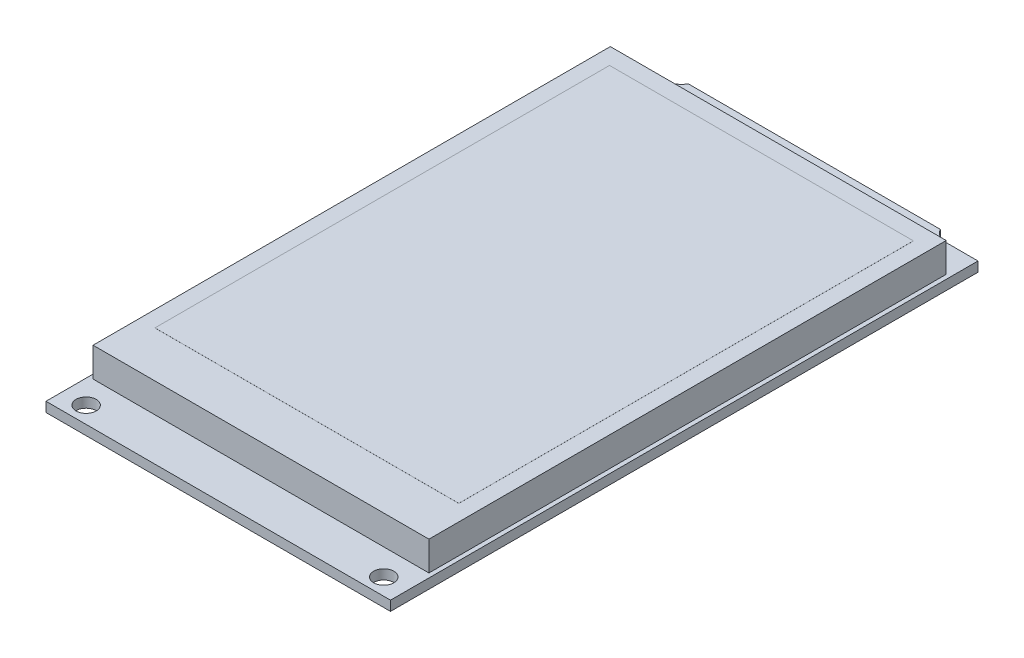
SolidWorks part; units mm, degrees
ref_plane "前视基准面" through (0, 0, 0) normal (0, 0, 1) x (1, 0, 0)
ref_plane "上视基准面" through (0, 0, 0) normal (0, 1, 0) x (1, 0, 0)
ref_plane "右视基准面" through (0, 0, 0) normal (1, 0, 0) x (0, 0, -1)
sketch "草图1" plane through (0, 0, 0) normal (0, 1, 0) x (1, 0, 0)
  line L0 (27.1813, 0) -> (83.5913, 0)
  line L1 (83.5913, 0) -> (83.5913, 96.2)
  line L2 (83.5913, 96.2) -> (78.2655, 96.2)
  line L3 (27.1813, 96.2) -> (27.1813, 0)
  line L5 (55.3863, 97.6) -> (34.7463, 97.6)
  line L6 (55.3863, 97.6) -> (76.0263, 97.6)
  line L7 (32.5072, 96.2) -> (27.1813, 96.2)
  arc A0 (76.0263, 97.6) -> (78.2655, 96.2) centre (78.353, 98.8306) ccw
  arc A1 (34.7463, 97.6) -> (32.5072, 96.2) centre (32.4197, 98.8306) cw
  circle A2 centre (31.0213, 2.73) radius 1.65
  circle A3 centre (79.7513, 2.73) radius 1.65
extrude "凸台-拉伸1" add sketch "草图1" along normal blind 1.6
sketch "草图3" plane through (0, 1.6, 0) normal (0, 1, 0) x (1, 0, 0)
  line L2 (55.3863, 7) -> (27.8863, 7)
  line L3 (55.3863, 7) -> (82.8863, 7)
  line L4 (82.8863, 7) -> (82.8863, 91.7)
  line L5 (27.8863, 7) -> (27.8863, 91.7)
  line L6 (27.8863, 91.7) -> (82.8863, 91.7)
extrude "凸台-拉伸2" add sketch "草图3" along normal blind 4.8
sketch "草图4" plane through (0, 6.4, 0) normal (0, 1, 0) x (1, 0, 0)
  line L2 (55.3863, 88.95) -> (30.5063, 88.95)
  line L3 (30.5063, 88.95) -> (30.5063, 14.51)
  line L4 (30.5063, 14.51) -> (80.2663, 14.51)
  line L5 (80.2663, 14.51) -> (80.2663, 88.95)
  line L6 (80.2663, 88.95) -> (55.3863, 88.95)
extrude "凸台-拉伸3" add sketch "草图4" along normal blind 0.01
